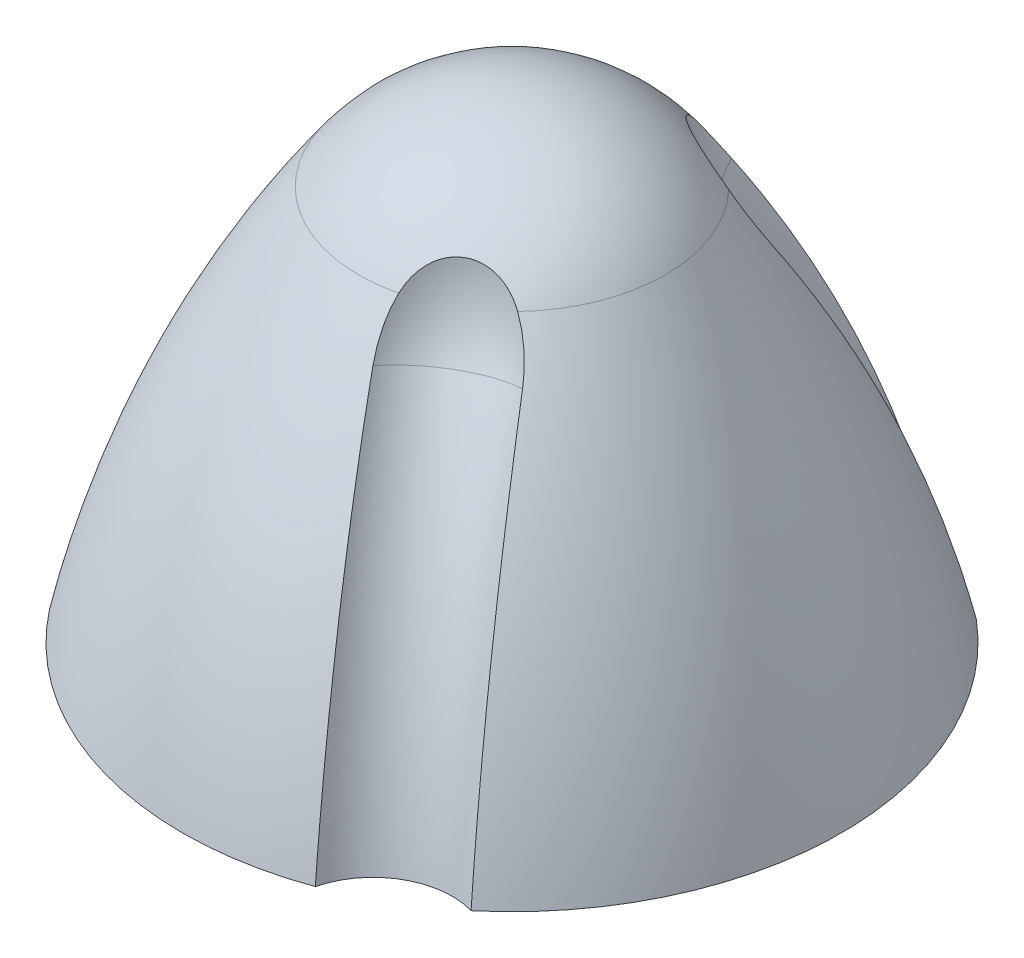
SolidWorks part; units mm, degrees
ref_plane "Front Plane" through (0, 0, 0) normal (0, 0, 1) x (1, 0, 0)
ref_plane "Top Plane" through (0, 0, 0) normal (0, 1, 0) x (1, 0, 0)
ref_plane "Right Plane" through (0, 0, 0) normal (1, 0, 0) x (0, 0, -1)
sketch "Sketch1" plane through (0, 0, 0) normal (0, 0, 1) x (1, 0, 0)
  line L0 (0, 41.275) -> (32.1625, 41.275) construction
  line L1 (0, -55) -> (0, 55) construction
  line L2 (0, 0) -> (0, 67.1107) construction
  line L3 (55, 0) -> (-55, 0) construction
  line L4 (0, 41.275) -> (0, 0)
  line L5 (0, 0) -> (7.5, 0)
  line L6 (0, 12.7) -> (8.5514, 12.7) construction
  arc A0 (0, 41.275) -> (6.1595, 38.1) centre (0, 33.7128) cw
  arc A1 (6.1595, 38.1) -> (14.3, 12.7294) centre (-29.5867, 12.6391) cw
  arc A2 (14.3, 12.7294) -> (14.3, 12.6706) centre (0, 12.7) cw
  arc A3 (14.3, 12.6706) -> (7.5, 0) centre (-0.9633, 12.702) cw
  dimension "D3" = 28.6
  dimension "D1" = 41.275
  dimension "D2" = 15
  dimension "D4" = 12.7
  dimension "D5" = 38.1
  dimension "D6" = 12.319
revolve "Revolve1" add sketch "Sketch1" angle 360 about L2
sketch "Sketch2" plane through (0, 0, 0) normal (1, 0, 0) x (0, 0, -1)
  line L0 (15.73, 0) -> (-15.73, 0) construction
  line L1 (-17.4625, 0) -> (17.4625, 0)
  line L2 (-17.4625, 0) -> (-17.4625, 22.225)
  line L3 (-17.4625, 22.225) -> (17.4625, 22.225)
  line L4 (17.4625, 0) -> (17.4625, 22.225)
  line L5 (0, 0) -> (0, 47.314) construction
  arc A0 (6.1595, 38.1) -> (-6.1595, 38.1) centre (0, 33.7128) ccw construction
  dimension "D1" = 19.05
  dimension "D2" = 34.925
extrude "Cut-Extrude1" cut sketch "Sketch2" against normal up to next and the other way up to next
sketch "Sketch3" plane through (0, 22.225, 0) normal (0, -1, 0) x (1, 0, 0)
  line L0 (-2.4348, -1.7526) -> (2.4348, -1.7526)
  line L1 (14.5644, 0) -> (-14.5644, 0) construction
  line L2 (0, -19.2087) -> (0, 19.2087) construction
  arc A0 (-2.4348, -1.7526) -> (2.4348, -1.7526) centre (0, 0) cw
  dimension "D1" = 3
  dimension "D2" = 1.7526
extrude "Cut-Extrude2" cut sketch "Sketch3" against normal blind 9.525
sketch "Sketch4" plane through (0, 0, 0) normal (0, 0, 1) x (1, 0, 0)
  line L0 (-6.35, 39.7002) -> (-6.35, 41.275)
  line L1 (0, 41.275) -> (-8.7578, 41.275) construction
  line L2 (0, -10.4775) -> (0, 10.4775) construction
  arc A0 (-13.2404, 22.225) -> (-7.3264, 36.3767) centre (29.5867, 12.6391) cw
  arc A1 (-6.1595, 38.1) -> (-13.2404, 22.225) centre (29.5867, 12.6391) ccw construction
  arc A2 (-7.3264, 36.3767) -> (-6.35, 39.7002) centre (-12.4947, 39.7002) ccw
  arc A3 (6.1595, 38.1) -> (-6.1595, 38.1) centre (0, 33.7128) ccw construction
  dimension "D1" = 1.5748
  dimension "D2" = 6.35
sketch "Sketch5" plane through (0, 22.225, 0) normal (0, -1, 0) x (1, 0, 0)
  line L0 (10.4775, 0) -> (-10.4775, 0) construction
  line L4 (0, -10.4775) -> (0, 10.4775) construction
  arc A0 (-13.0408, 2.29) -> (-13.0408, -2.29) centre (-15.24, 0) cw
  circle A2 centre (0, 0) radius 13.2404 construction
  arc A3 (-13.0408, 2.29) -> (-13.0408, -2.29) centre (0, 0) ccw
  dimension "D1" = 3.175
  dimension "D2" = 15.24
sweep "Cut-Sweep1" cut profiles "Sketch5" path "Sketch4"
ref_axis "Axis1" through (0, 42.2433, 0) along (0, -1, 0)
pattern_circular "CirPattern1" count 3 over 360 about axis through (0, 42.2433, 0) along (0, -1, 0) of "Cut-Sweep1"
sketch "Sketch6" plane through (0, 22.225, 0) normal (0, -1, 0) x (1, 0, 0)
  circle A0 centre (0, 0) radius 6.35
  dimension "D1" = 12.7
extrude "Cut-Extrude3" cut sketch "Sketch6" against normal blind 3.175
